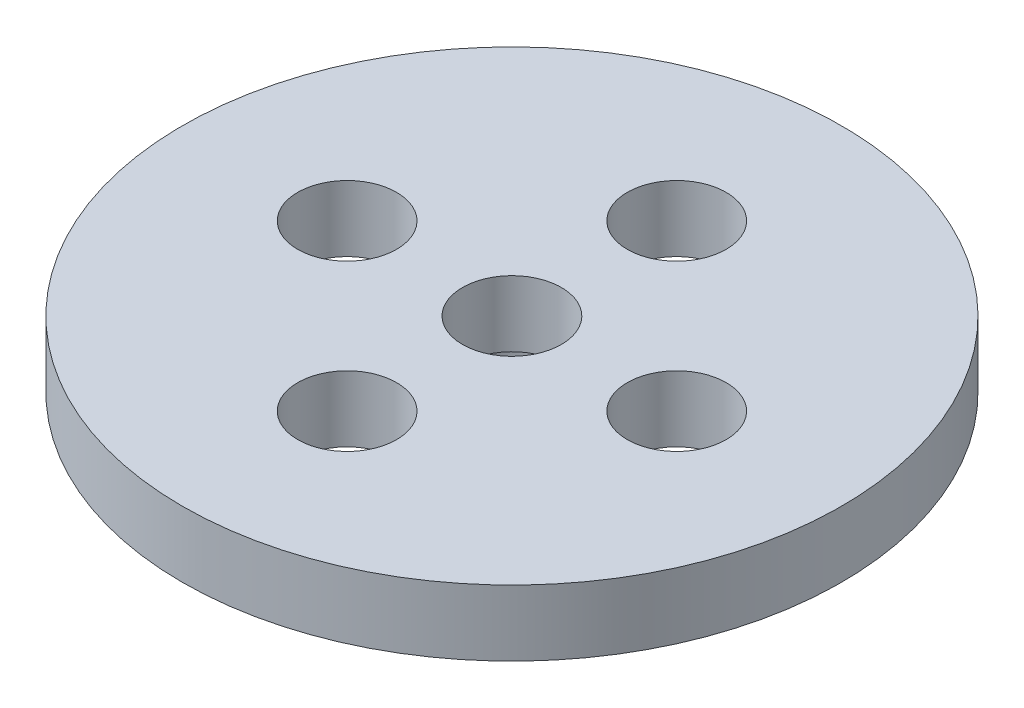
SolidWorks part; units mm, degrees
ref_plane "Front" through (0, 0, 0) normal (0, 0, 1) x (1, 0, 0)
ref_plane "Top" through (0, 0, 0) normal (0, 1, 0) x (1, 0, 0)
ref_plane "Right" through (0, 0, 0) normal (1, 0, 0) x (0, 0, -1)
sketch "Çizim1" plane through (0, 0, 0) normal (0, 1, 0) x (1, 0, 0)
  circle A0 centre (-0.1536, 0.0842) radius 1.5
  circle A1 centre (-0.1536, 5.0842) radius 1.5
  circle A2 centre (-5.1536, 0.0842) radius 1.5
  circle A3 centre (4.8464, 0.0842) radius 1.5
  circle A4 centre (-0.1536, -4.9158) radius 1.5
  circle A5 centre (-0.1536, 0.0842) radius 10
  dimension "D1" = 20
  dimension "D6" = 3
  dimension "D7" = 3
  dimension "D8" = 3
  dimension "D9" = 3
  dimension "D10" = 3
  dimension "D2" = 5
  dimension "D3" = 5
  dimension "D4" = 5
  dimension "D5" = 5
extrude "Yükseklik-Ekstrüzyon1" add sketch "Çizim1" along normal blind 2
sketch "Çizim2" plane through (0, 0, 0) normal (0, -1, 0) x (1, 0, 0)
  circle A0 centre (-0.1536, -0.0842) radius 1.7247
  circle A1 centre (-0.1536, -0.0842) radius 2.5
  dimension "D1" = 5
extrude "Yükseklik-Ekstrüzyon2" add sketch "Çizim2" along normal blind 2
